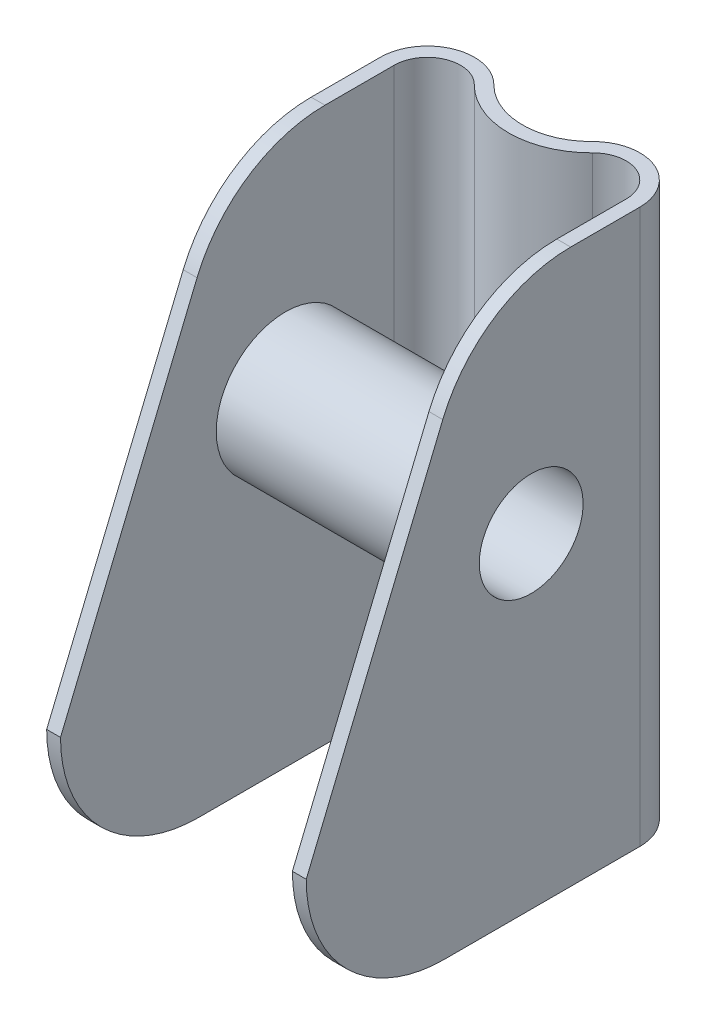
SolidWorks part; units mm, degrees
ref_plane "Front" through (0, 0, 0) normal (0, 0, 1) x (1, 0, 0)
ref_plane "Top" through (0, 0, 0) normal (0, 1, 0) x (1, 0, 0)
ref_plane "Right" through (0, 0, 0) normal (1, 0, 0) x (0, 0, -1)
sketch "Sketch1" plane through (0, 0, 0) normal (0, 1, 0) x (1, 0, 0)
  line L0 (0, 0) -> (0, 61.2214)
  line L1 (8.6286, 69.85) -> (38.9964, 69.85) construction
  line L2 (47.625, 61.2214) -> (47.625, 0)
  arc A0 (0, 61.2214) -> (14.7713, 67.2811) centre (8.6286, 61.2214) cw
  arc A1 (14.7713, 67.2811) -> (32.8537, 67.2811) centre (23.8125, 76.2) ccw
  arc A2 (32.8537, 67.2811) -> (47.625, 61.2214) centre (38.9964, 61.2214) cw
  point P11 (31.8837, 26.3583)
  point P12 (23.8125, 63.5)
  dimension "D1" = 12.7
  dimension "D2" = 69.85
  dimension "D3" = 47.625
  dimension "D4" = 6.35
extrude "Extrude-Thin1" add sketch "Sketch1" against normal blind 101.6 thin
sketch "Sketch2" plane through (0, 0, 0) normal (-1, 0, 0) x (0, 0, 1)
  line L0 (0, 0) -> (-61.2214, 0) construction
  line L1 (-41.275, 0) -> (-41.275, -41.91)
  line L2 (-69.85, 0) -> (-69.85, -101.6) construction
  circle A0 centre (-41.275, -41.91) radius 12.7
  circle A1 centre (-41.275, -41.91) radius 9.525
  dimension "D2" = 25.4
  dimension "D3" = 19.05
  dimension "D1" = 41.91
  dimension "D4" = 28.575
sketch "Sketch3" plane through (0, 0, 0) normal (-1, 0, 0) x (0, 0, 1)
  circle A0 centre (-41.275, -41.91) radius 9.525
  dimension "D1" = 19.05
extrude "Extrude1" cut sketch "Sketch3" against normal blind 101.6
extrude "Extrude2" add sketch "Sketch2" against normal up to surface (45.085 mm away)
sketch "Sketch4" plane through (0, 0, 0) normal (-1, 0, 0) x (0, 0, 1)
  line L0 (0, -76.2) -> (-25.053, -15.6843)
  line L1 (0, -101.6) -> (0, 0) construction
  line L2 (0, 0) -> (-61.2214, 0) construction
  line L3 (-48.5214, 0) -> (0, 0)
  line L4 (0, 0) -> (0, -76.2)
  line L5 (0, -101.6) -> (-61.2214, -101.6) construction
  line L6 (-25.4, -101.6) -> (0, -101.6)
  line L7 (0, -101.6) -> (0, -76.2)
  arc A0 (-25.053, -15.6843) -> (-48.5214, 0) centre (-48.5214, -25.4) ccw
  arc A1 (0, -76.2) -> (-25.4, -101.6) centre (-25.4, -76.2) cw
  line M1 (0, 0) -> (-61.2214, 0)
  line M4 (0, -101.6) -> (0, 0)
  dimension "D1" = 25.4
  dimension "D2" = 12.7
  dimension "D3" = 25.4
extrude "Extrude3" cut sketch "Sketch4" against normal blind 101.6 contours A0 L0 M4 M1 | A1 L6 L7
